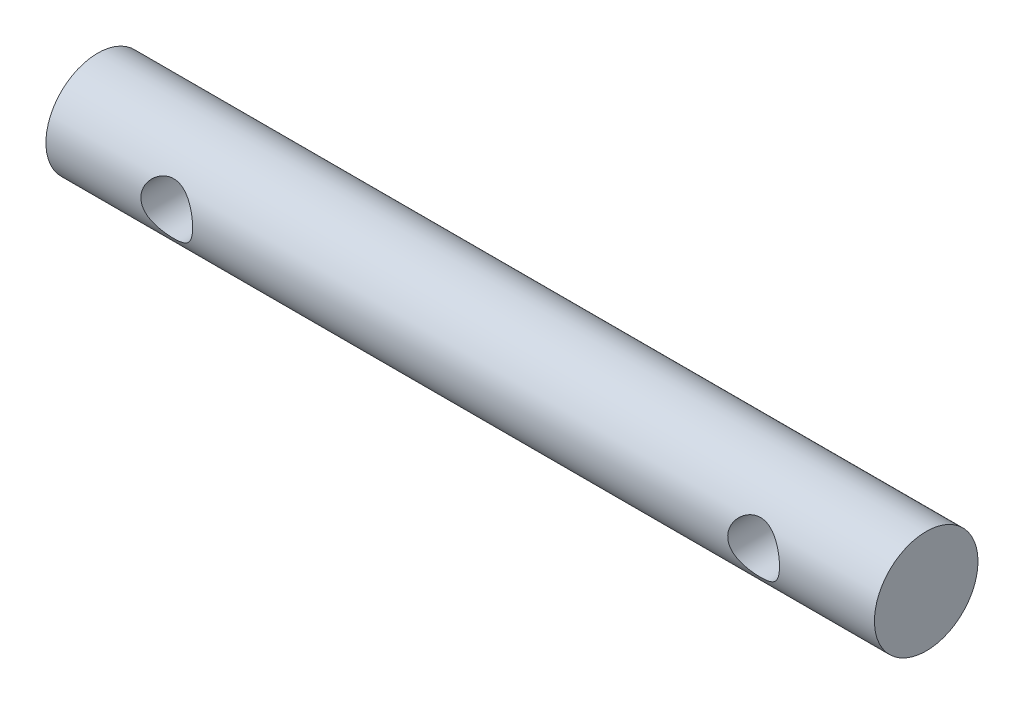
SolidWorks part; units mm, degrees
ref_plane "Front Plane" through (0, 0, 0) normal (1, 0, 0) x (0, 1, 0)
ref_plane "Top Plane" through (0, 0, 0) normal (0, 0, 1) x (0, 1, 0)
ref_plane "Right Plane" through (0, 0, 0) normal (0, 1, 0) x (-1, 0, 0)
sketch "Sketch1" plane through (0, 0, 0) normal (1, 0, 0) x (0, 1, 0)
  circle A0 centre (0, 0) radius 3
  dimension "D1" = 6
extrude "Boss-Extrude1" add sketch "Sketch1" along normal blind 48
sketch "Sketch2" plane through (0, 0, 0) normal (0, 0, 1) x (0, 1, 0)
  line L0 (3, 0) -> (-3, 0) construction
  line L1 (-3, -48) -> (3, -48) construction
  circle A0 centre (0, -41) radius 1.5
  circle A2 centre (0, -7) radius 1.5
  dimension "D1" = 3
  dimension "D2" = 3
  dimension "D3" = 7
  dimension "D4" = 7
extrude "Cut-Extrude1" cut sketch "Sketch2" against normal through all both and the other way through all
ref_plane "Plane1" through (24, 0, 0) normal (-1, 0, 0) x (0, -1, 0)
